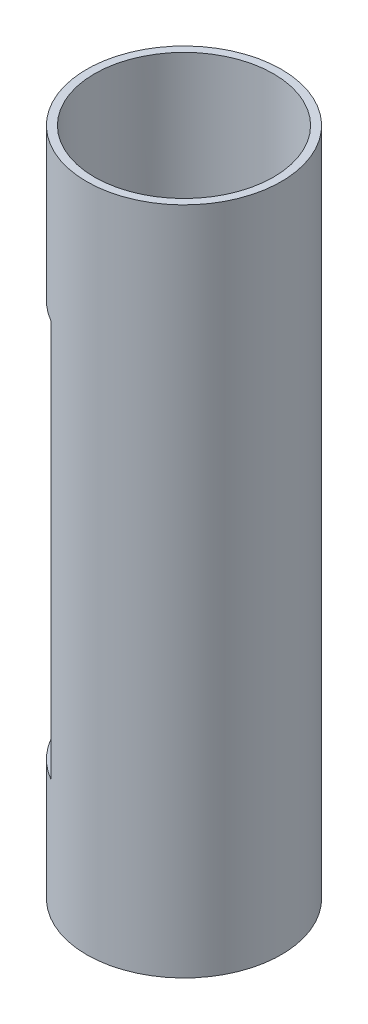
SolidWorks part; units mm, degrees
material "ПВХ 0.007 Смягченный"
ref_plane "Спереди" through (0, 0, 0) normal (0, 0, 1) x (1, 0, 0)
ref_plane "Сверху" through (0, 0, 0) normal (0, 1, 0) x (1, 0, 0)
ref_plane "Справа" through (0, 0, 0) normal (1, 0, 0) x (0, 0, -1)
sketch "Эскиз1" plane through (0, 0, 0) normal (0, 1, 0) x (1, 0, 0)
  circle A0 centre (0, 0) radius 25
  circle A1 centre (0, 0) radius 23
  dimension "ExDBody" = 50
  dimension "InDBody" = 46
extrude "Бобышка-Вытянуть1" add sketch "Эскиз1" along normal blind 172
ref_plane "Плоскость1" through (0, 31, 0) normal (0, -1, 0) x (-1, 0, 0)
sketch "Эскиз2" plane through (0, 31, 0) normal (0, -1, 0) x (-1, 0, 0)
  line L0 (0, 0) -> (29.6146, 51.294)
  line L1 (29.6146, 51.294) -> (33.4528, -57.9419)
  line L2 (33.4528, -57.9419) -> (0, 0)
  line L3 (-80.9, 0) -> (80.9, 0) construction
  dimension "D1" = 120
  dimension "D2" = 60
extrude "Вырез-Вытянуть1" cut sketch "Эскиз2" against normal blind 102
